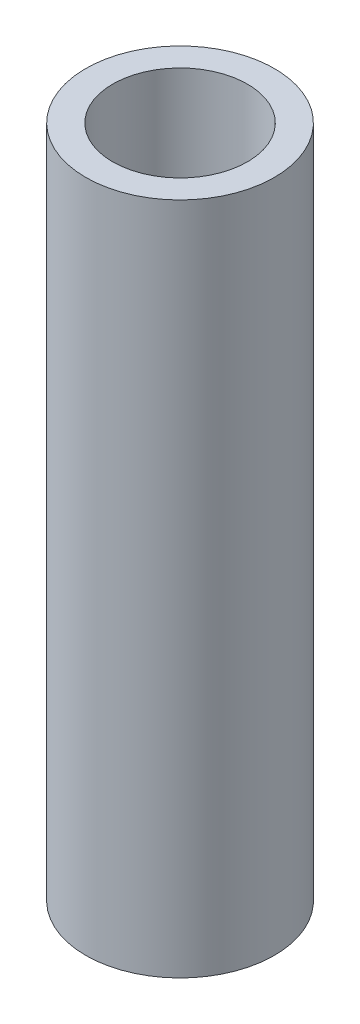
SolidWorks part; units mm, degrees
material "ABS PC"
ref_plane "Plano frontal" through (0, 0, 0) normal (0, 0, 1) x (1, 0, 0)
ref_plane "Plano superior" through (0, 0, 0) normal (0, 1, 0) x (1, 0, 0)
ref_plane "Plano direito" through (0, 0, 0) normal (1, 0, 0) x (0, 0, -1)
sketch "Esboço1" plane through (0, 0, 0) normal (0, 1, 0) x (1, 0, 0)
  circle A0 centre (0, 0) radius 3.5
  circle A1 centre (0, 0) radius 2.5
  dimension "D1" = 7
  dimension "D2" = 5
extrude "Ressalto-extrusão1" add sketch "Esboço1" along normal blind 25
